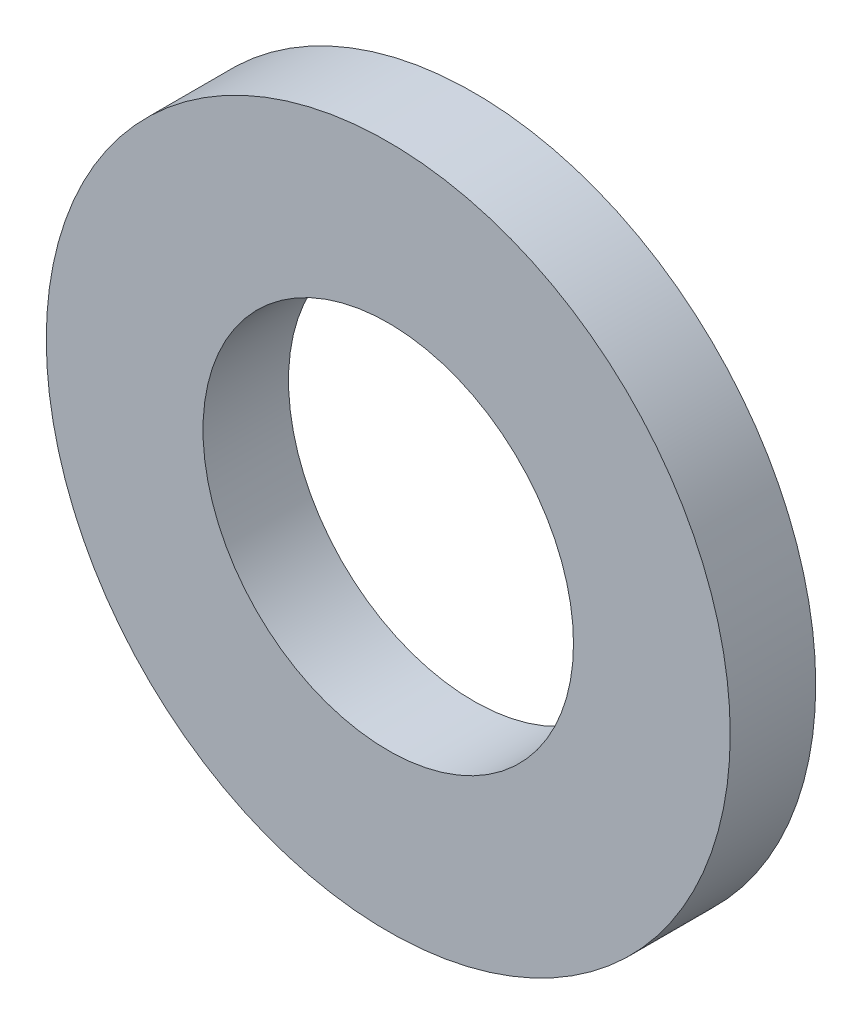
SolidWorks part; units mm, degrees
ref_plane "前视基准面" through (0, 0, 0) normal (0, 0, 1) x (1, 0, 0)
ref_plane "上视基准面" through (0, 0, 0) normal (0, 1, 0) x (1, 0, 0)
ref_plane "右视基准面" through (0, 0, 0) normal (1, 0, 0) x (0, 0, -1)
sketch "草图1" plane through (0, 0, 0) normal (0, 0, 1) x (1, 0, 0)
  circle A0 centre (0, 0) radius 12
  dimension "D1" = 24
extrude "凸台-拉伸1" add sketch "草图1" along normal blind 3
sketch "草图3" plane through (0, 0, 3) normal (0, 0, 1) x (1, 0, 0)
  circle A0 centre (0, 0) radius 6.5
  dimension "D1" = 13
extrude "切除-拉伸1" cut sketch "草图3" against normal blind 3
